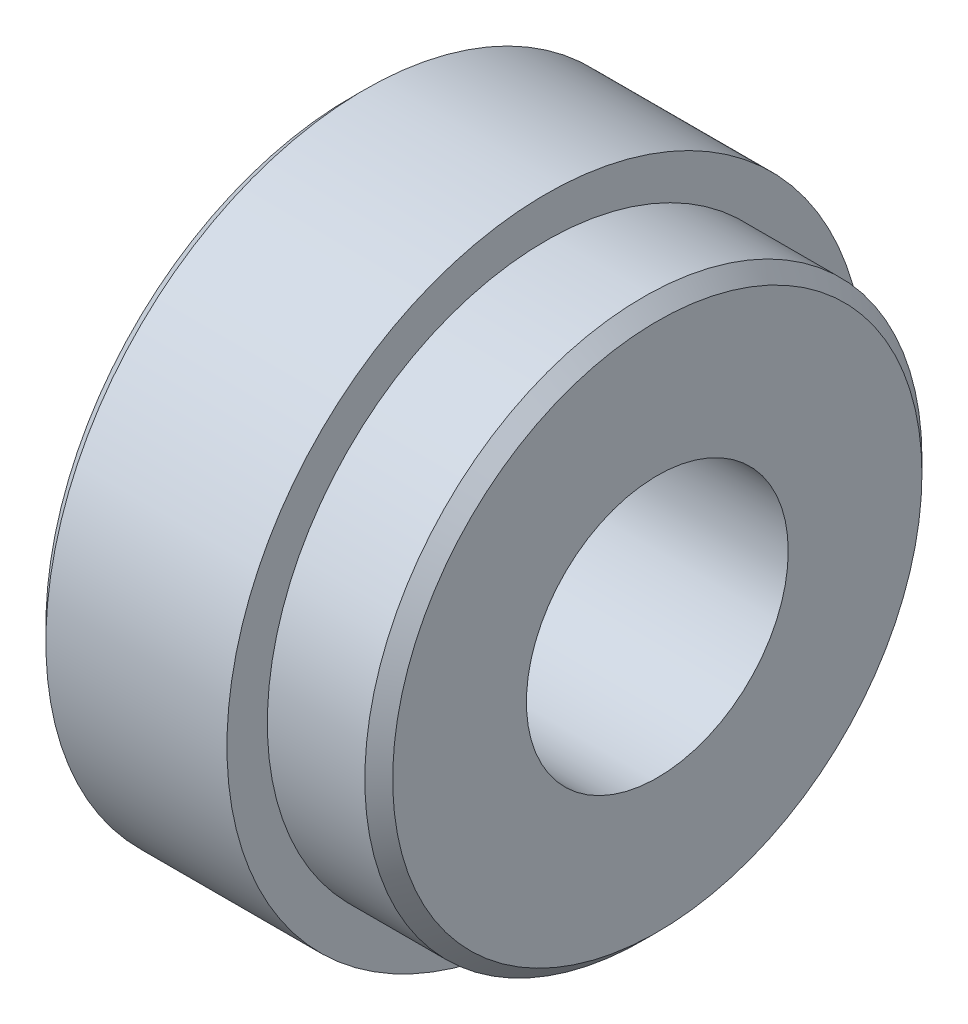
SolidWorks part; units mm, degrees
ref_plane "Front Plane" through (0, 0, 0) normal (0, 0, 1) x (1, 0, 0)
ref_plane "Top Plane" through (0, 0, 0) normal (0, 1, 0) x (1, 0, 0)
ref_plane "Right Plane" through (0, 0, 0) normal (1, 0, 0) x (0, 0, -1)
sketch "Sketch1" plane through (0, 0, 0) normal (1, 0, 0) x (0, 0, -1)
  circle A0 centre (0, 0) radius 11.45
  dimension "D1" = 22.9
extrude "Boss-Extrude1" add sketch "Sketch1" along normal blind 7
sketch "Sketch2" plane through (7, 0, 0) normal (1, 0, 0) x (0, 0, -1)
  circle A0 centre (0, 0) radius 10
  dimension "D1" = 20
extrude "Boss-Extrude2" add sketch "Sketch2" along normal blind 4
sketch "Sketch3" plane through (11, 0, 0) normal (1, 0, 0) x (0, 0, -1)
  circle A0 centre (0, 0) radius 4.7
  dimension "D1" = 9.4
extrude "Cut-Extrude1" cut sketch "Sketch3" against normal through all
chamfer "Chamfer1" distance 0.5 angle 45 3 edges at (0, 0, -11.45) (0, 0, -4.7) (11, 0, -10)
